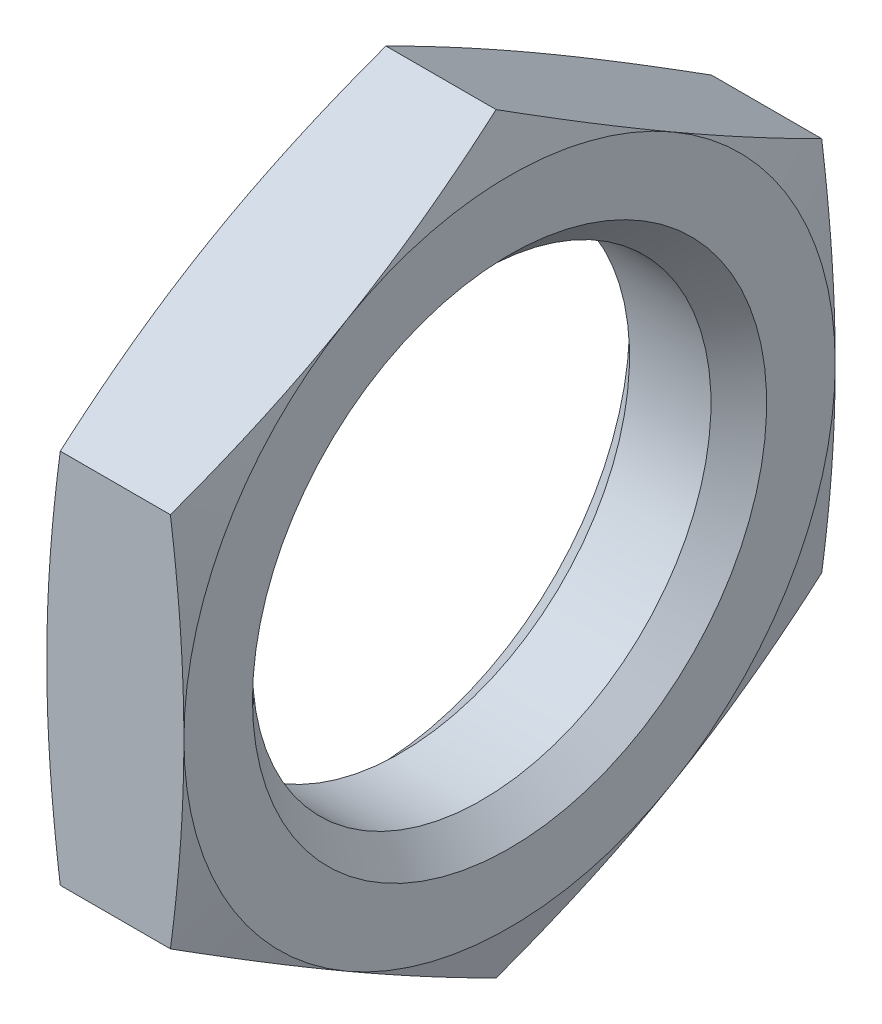
SolidWorks part; units mm, degrees
ref_plane "前视基准面" through (0, 0, 0) normal (0, 0, 1) x (1, 0, 0)
ref_plane "上视基准面" through (0, 0, 0) normal (0, 1, 0) x (1, 0, 0)
ref_plane "右视基准面" through (0, 0, 0) normal (1, 0, 0) x (0, 0, -1)
ref_plane "基准面1" through (0, 0, 0) normal (0, 0, 1) x (1, 0, 0)
sketch "草图1" plane through (0, 0, 0) normal (0, 0, 1) x (1, 0, 0)
  line L0 (0, 9.5) -> (0, 7.5)
  line L1 (0, 7.5) -> (0.812, 6.688)
  line L2 (0.812, 6.688) -> (3.188, 6.688)
  line L3 (3.188, 6.688) -> (4, 7.5)
  line L4 (4, 7.5) -> (4, 9.5)
  line L5 (4, 9.5) -> (2.4727, 15.2)
  line L6 (2.4727, 15.2) -> (1.5273, 15.2)
  line L7 (1.5273, 15.2) -> (0, 9.5)
  line L8 (4, 0) -> (0, 0) construction
revolve "旋转1" add sketch "草图1" angle 360 about L8
cosmetic thread "装饰螺纹线1" parameters "D1"=4, "D2"=15
ref_plane "基准面2" through (0, 0, 0) normal (1, 0, 0) x (0, 0, -1)
sketch "草图2" plane through (0, 0, 0) normal (1, 0, 0) x (0, 0, -1)
  line L0 (-9.5, -5.4848) -> (0, -10.9697)
  line L1 (0, -10.9697) -> (9.5, -5.4848)
  line L2 (9.5, -5.4848) -> (9.5, 5.4848)
  line L3 (9.5, 5.4848) -> (0, 10.9697)
  line L4 (0, 10.9697) -> (-9.5, 5.4848)
  line L5 (-9.5, 5.4848) -> (-9.5, -5.4848)
  circle A0 centre (0, 0) radius 40
extrude "切除-拉伸1" cut sketch "草图2" along normal blind 4
